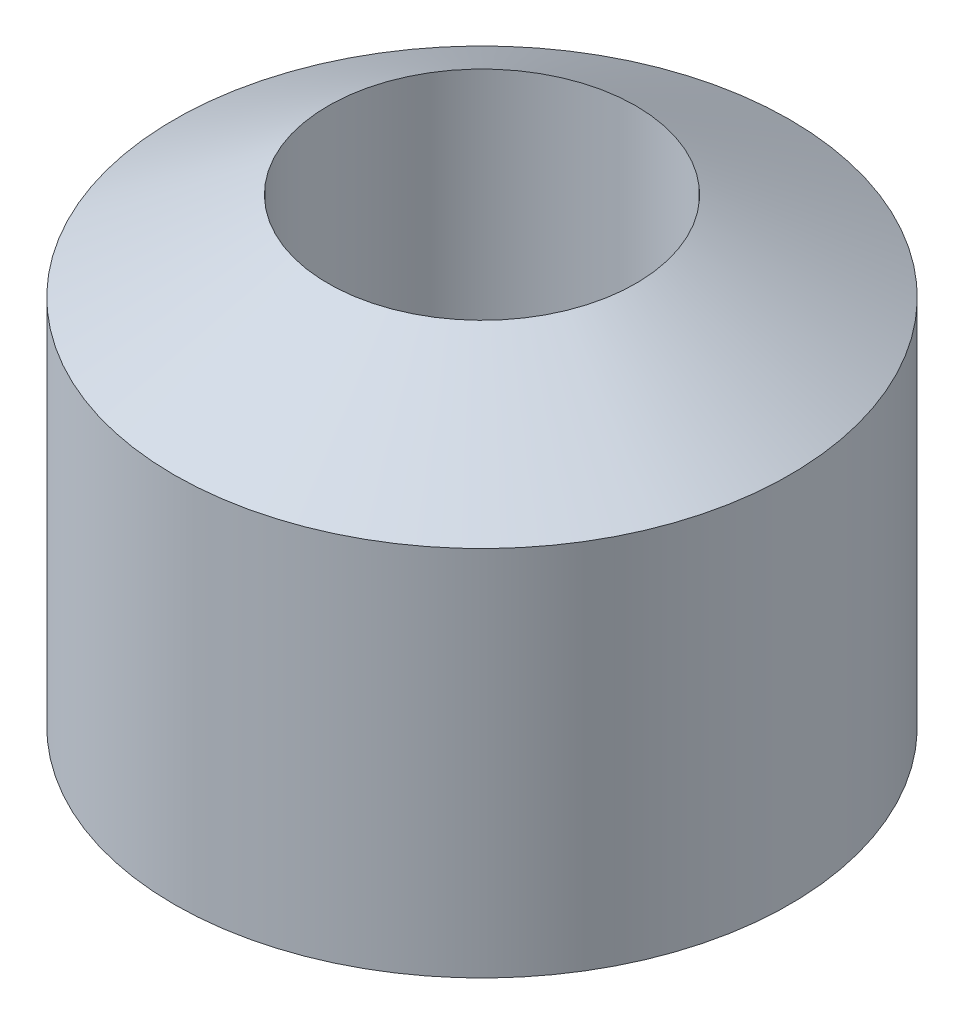
SolidWorks part; units mm, degrees
ref_plane "Front Plane" through (0, 0, 0) normal (0, 0, 1) x (1, 0, 0)
ref_plane "Top Plane" through (0, 0, 0) normal (0, 1, 0) x (1, 0, 0)
ref_plane "Right Plane" through (0, 0, 0) normal (1, 0, 0) x (0, 0, -1)
sketch "Sketch1" plane through (0, 0, 0) normal (0, 0, 1) x (1, 0, 0)
  line L0 (0, 0) -> (0, 59362.8265) construction
  line L1 (0, 0) -> (59362.8265, 0) construction
  line L2 (14, 50) -> (14, 0)
  line L3 (14, 0) -> (28, 8.0829)
  line L4 (28, 8.0829) -> (28, 41.9171)
  line L5 (28, 41.9171) -> (14, 50)
  dimension "D1" = 50
  dimension "D2" = 60
  dimension "D3" = 60
  dimension "D4" = 28
  dimension "D5" = 56
revolve "Revolve1" add sketch "Sketch1" angle 360 about L0
